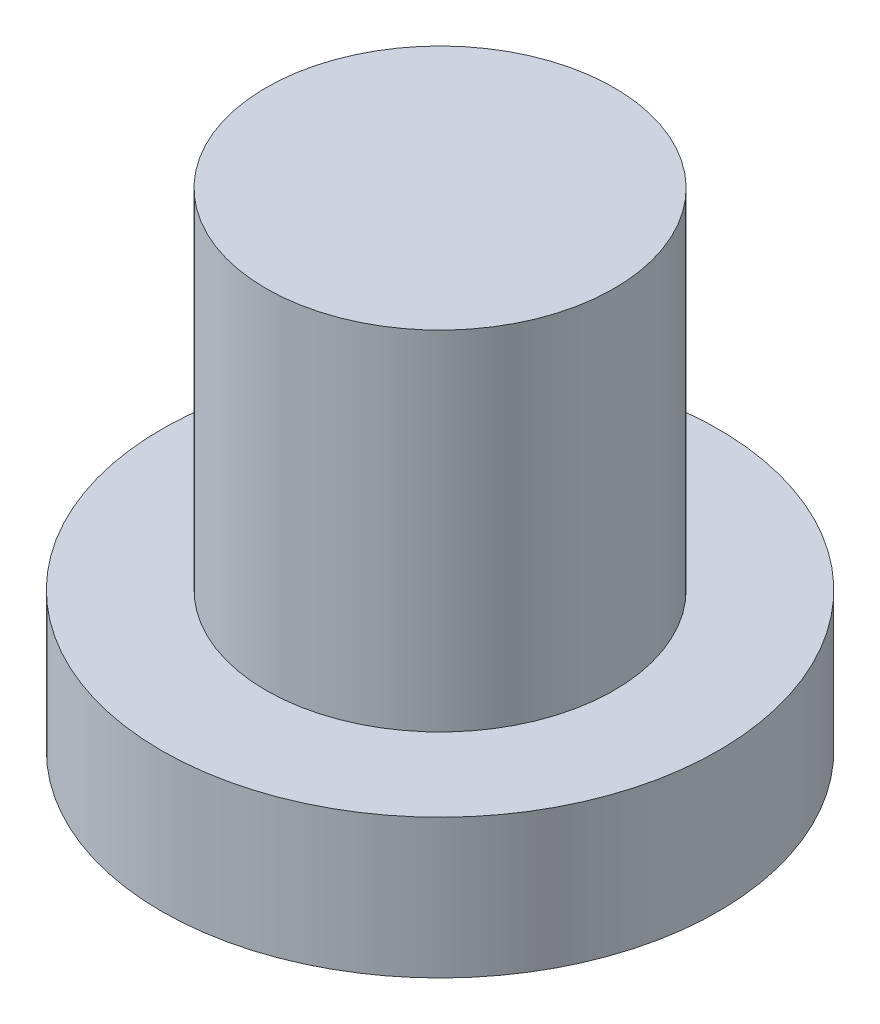
SolidWorks part; units mm, degrees
ref_plane "Front Plane" through (0, 0, 0) normal (0, 0, 1) x (1, 0, 0)
ref_plane "Top Plane" through (0, 0, 0) normal (0, 1, 0) x (1, 0, 0)
ref_plane "Right Plane" through (0, 0, 0) normal (1, 0, 0) x (0, 0, -1)
sketch "Sketch2" plane through (0, 0, 0) normal (0, 1, 0) x (1, 0, 0)
  circle A0 centre (0, 0) radius 40
  dimension "D1" = 80
extrude "Boss-Extrude1" add sketch "Sketch2" along normal blind 20
sketch "Sketch3" plane through (0, 20, 0) normal (0, 1, 0) x (1, 0, 0)
  circle A0 centre (0, 0) radius 25
  dimension "D1" = 50
extrude "Boss-Extrude2" add sketch "Sketch3" along normal blind 50
sketch "Sketch5" plane through (0, 0, 0) normal (0, 0, 1) x (1, 0, 0)
  line L0 (0, 0) -> (0, -200) construction
  arc A0 (4.343, -128.1311) -> (-72, -200) centre (0, -200) cw
  arc A1 (-72, -200) -> (-120, -85.7371) centre (-232, -200) ccw
  arc A2 (-27.408, -125.4894) -> (4.343, -128.1311) centre (0, 11.8015) ccw
  point P6 (10.9362, -128.8354)
  point P8 (-44.4443, 0)
  point P11 (0, 0)
  point P12 (0, 0)
  point P13 (36.763, -138.093)
  point P14 (0, 0)
  point P15 (0, -128)
  point P16 (-25.0283, -125.7446)
  point P17 (-120, -85.7371)
  point P18 (-120, -85.7371)
  point P19 (-7.479, -128)
  point P20 (126.2816, 72.4397)
  point P21 (0, -128)
  point P22 (0, 0)
  point P23 (44.4775, -143.3806)
  point P24 (-84.4168, 95.4195)
  point P25 (-140, -113.4299)
  point P26 (-137.0402, -34.2206)
  point P27 (-98.6239, -32.6354)
  point P28 (58.9232, -158.623)
  point P29 (-27.408, -125.4894)
  dimension "D2" = 72
  dimension "D4" = 160
  dimension "D5" = 140
  dimension "D1" = 200
  dimension "D3" = 120
